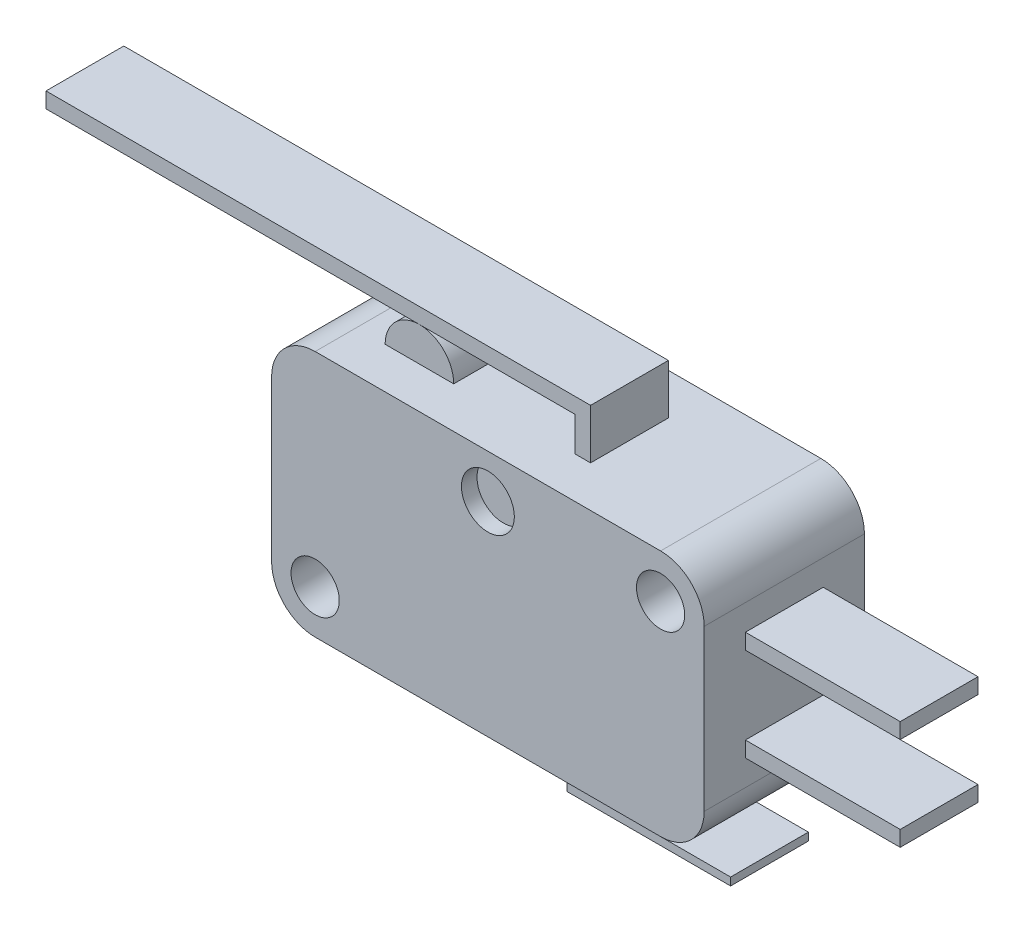
SolidWorks part; units mm, degrees
ref_plane "Alzado" through (0, 0, 0) normal (0, 0, 1) x (1, 0, 0)
ref_plane "Planta" through (0, 0, 0) normal (0, 1, 0) x (1, 0, 0)
ref_plane "Vista lateral" through (0, 0, 0) normal (1, 0, 0) x (0, 0, -1)
sketch "Croquis1" plane through (0, 0, 0) normal (0, 0, 1) x (1, 0, 0)
  line L0 (-11.1, 0) -> (11.1, 0) construction
  line L1 (-11.1, 7.95) -> (11.1, 7.95)
  line L2 (-13.9, 5.15) -> (-13.9, -5.15)
  line L3 (-11.1, -7.95) -> (11.1, -7.95)
  line L4 (13.9, 5.15) -> (13.9, -5.15)
  line L5 (11.1, 5.15) -> (11.1, -5.15) construction
  line L6 (-11.1, -5.15) -> (-11.1, 5.15) construction
  line L8 (-8.3, -5.15) -> (-8.3, -7.95)
  circle A0 centre (11.1, 5.15) radius 1.55
  circle A1 centre (-11.1, -5.15) radius 1.55
  arc A2 (-13.9, -5.15) -> (-11.1, -7.95) centre (-11.1, -5.15) ccw
  arc A3 (13.9, 5.15) -> (11.1, 7.95) centre (11.1, 5.15) ccw
  arc A5 (-13.9, 5.15) -> (-11.1, 7.95) centre (-11.1, 5.15) cw
  arc A6 (11.1, -7.95) -> (13.9, -5.15) centre (11.1, -5.15) ccw
  point P0 (0, 0)
  point P9 (0, 0)
  point P10 (0, 0)
  point P13 (11.1, 0)
  point P16 (-11.1, 0)
  dimension "D6" = 2.8
  dimension "D1" = 5.6
  dimension "D2" = 2.8
  dimension "D3" = 22.2
  dimension "D4" = 10.3
  dimension "D5" = 10.3
extrude "Saliente-Extruir1" add sketch "Croquis1" along normal blind 10.3
sketch "Croquis2" plane through (0, 0, 10.3) normal (0, 0, 1) x (1, 0, 0)
  line L0 (0, 5.15) -> (0, -5.15)
  circle A0 centre (0, 5.15) radius 1.7
  point P4 (0, 0)
  dimension "D1" = 10.3
extrude "Cortar-Extruir1" cut sketch "Croquis2" against normal blind 1
sketch "Croquis3" plane through (0, 0, 0) normal (0, 0, -1) x (-1, 0, 0)
  line L0 (0, 5.15) -> (0, -5.15) construction
  circle A0 centre (0, 5.15) radius 1.7
  point P4 (0, 0)
  dimension "D2" = 3.4
  dimension "D1" = 10.3
extrude "Cortar-Extruir2" cut sketch "Croquis3" against normal blind 1
ref_plane "Plano1" through (0, 0, 5.15) normal (0, 0, -1) x (-1, 0, 0)
sketch "Croquis4" plane through (0, 0, 5.15) normal (0, 0, -1) x (-1, 0, 0)
  line L0 (0, 0) -> (0, -10) construction
  line L1 (-11.05, 0) -> (11.05, 0) construction
  line L2 (11.05, 0) -> (2.95, 0) construction
  line L3 (2.95, 0) -> (2.95, -7.95) construction
  line L10 (2.95, 0) -> (2.95, 7.95) construction
  line L17 (-2.45, -7.95) -> (-2.95, -7.95)
  line L18 (-2.45, -11.1) -> (-2.45, -7.95)
  line L19 (-12.95, -11.1) -> (-2.45, -11.1)
  line L20 (-12.95, -10.6) -> (-12.95, -11.1)
  line L21 (-2.95, -10.6) -> (-12.95, -10.6)
  line L22 (-2.95, -7.95) -> (-2.95, -10.6)
  line L23 (-3.95, 7.95) -> (-2.95, 7.95)
  line L24 (-3.95, 11.1536) -> (-3.95, 7.95)
  line L25 (31.05, 11.1536) -> (-3.95, 11.1536)
  line L26 (31.05, 10.1536) -> (31.05, 11.1536)
  line L27 (-2.95, 10.1536) -> (31.05, 10.1536)
  line L28 (-2.95, 7.95) -> (-2.95, 10.1536)
  line L29 (-2.95, 7.95) -> (7.05, 7.95) construction
  line L30 (7.05, 7.95) -> (9.2536, 7.95) construction
  line L31 (9.2536, 7.95) -> (4.8464, 7.95)
  line L32 (-11.05, 0) -> (-13.85, 0) construction
  line L33 (-13.85, 3) -> (-13.85, -3) construction
  line L34 (-13.85, 3.5) -> (-13.85, 2.5)
  line L35 (-13.85, -2.5) -> (-13.85, -3.5)
  line L37 (-13.85, 3.5) -> (-23.85, 3.5)
  line L38 (-13.85, 3.5) -> (-13.85, 2.5)
  line L39 (-13.85, 2.5) -> (-23.85, 2.5)
  line L40 (-23.85, 3.5) -> (-23.85, 2.5)
  line L41 (-13.85, -2.5) -> (-23.85, -2.5)
  line L42 (-13.85, -2.5) -> (-13.85, -3.5)
  line L43 (-13.85, -3.5) -> (-23.85, -3.5)
  line L44 (-23.85, -2.5) -> (-23.85, -3.5)
  arc A0 (9.2536, 7.95) -> (4.8464, 7.95) centre (7.05, 7.95) ccw
  point P6 (0, 0)
  point P27 (-13.85, 0)
  point P31 (-13.85, 3)
  point P34 (-13.85, -3)
  dimension "D4" = 6
  dimension "D1" = 22.1
  dimension "D2" = 8.1
  dimension "D3" = 10
extrude "Saliente-Extruir2" add sketch "Croquis4" along normal mid plane 5 separate body contours L23 L28 L27 L26 L25 L24 | L31 A0 | L37 L40 L39 L34 | L41 L44 L43 L42 | L19 L18 L17 L22 L21 L20
